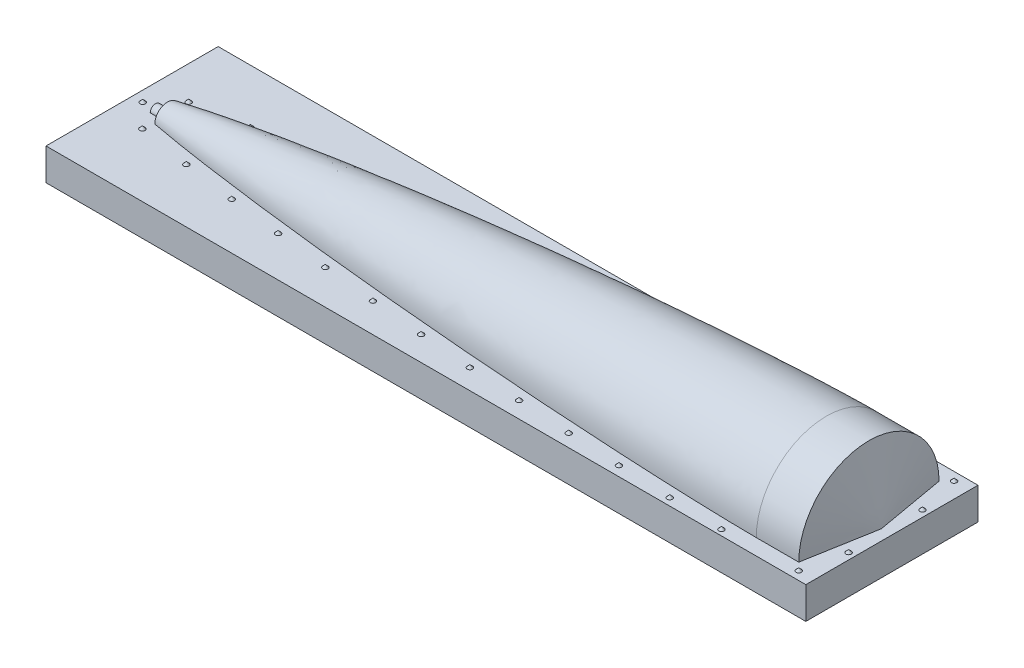
SolidWorks part; units mm, degrees
ref_plane "Front Plane" through (0, 0, 0) normal (0, 0, 1) x (1, 0, 0)
ref_plane "Top Plane" through (0, 0, 0) normal (0, 1, 0) x (1, 0, 0)
ref_plane "Right Plane" through (0, 0, 0) normal (1, 0, 0) x (0, 0, -1)
sketch "Sketch4" plane through (0, 0, 0) normal (0, 1, 0) x (1, 0, 0)
  line L0 (838.2, 83.82) -> (889, 83.82)
  line L1 (889, 83.82) -> (903.7797, 0)
  line L2 (0, 0) -> (903.7797, 0) construction
  line L3 (49.2388, 6.35) -> (36.5388, 6.35)
  line L4 (49.2388, 6.35) -> (50.8, 15.2039)
  line L5 (36.5388, 6.35) -> (33.9086, 0)
  line L6 (33.9086, 0) -> (903.7797, 0)
  spline S0 degree 4 poles (-0.1653, 2.0883) (-0.1623, 2.0965) (-0.155, 2.1122) (-0.1352, 2.1408) (-0.1001, 2.1794) (-0.0565, 2.2217) (0.0094, 2.2781) (0.0918, 2.3417) (0.2643, 2.4628) (0.4837, 2.5961) (0.7329, 2.7344) (1.0319, 2.8879) (1.2997, 3.0182) (1.7414, 3.223) (2.5277, 3.5614) (3.9556, 4.1194) (6.672, 5.0601) (11.6636, 6.5715) (21.0315, 9.0225) (37.3773, 12.6846) (65.1467, 18.0274) (103.2721, 24.3172) (149.4818, 31.024) (200.8689, 37.6925) (252.3281, 43.7745) (303.8424, 49.369) (355.4008, 54.5396) (406.9964, 59.3234) (458.6244, 63.7438) (510.2814, 67.8116) (561.9649, 71.5281) (613.673, 74.8838) (665.4047, 77.857) (710.6897, 80.0885) (749.5194, 81.692) (780.8316, 82.7407) (801.9102, 83.3045) (819.2265, 83.6482) (830.0682, 83.7821) (835.4894, 83.82) (838.2, 83.82) knots 0 0 0 0 0 0.000041 0.000082 0.000164 0.000247 0.000329 0.000493 0.000658 0.001245 0.001545 0.001844 0.002251 0.002657 0.003853 0.005902 0.009516 0.016281 0.028569 0.051794 0.088907 0.150314 0.211721 0.273128 0.334535 0.395942 0.457348 0.518755 0.580162 0.641569 0.702976 0.764383 0.825789 0.887196 0.9179 0.948603 0.974302 0.987151 1 1 1 1 1 construction
  spline S1 degree 4 poles (50.8, 15.2039) (56.2583, 16.2407) (74.4684, 19.5622) (105.5221, 24.6437) (149.4818, 31.024) (200.8689, 37.6925) (252.3281, 43.7745) (303.8424, 49.369) (355.4008, 54.5396) (406.9964, 59.3234) (458.6244, 63.7438) (510.2814, 67.8116) (561.9649, 71.5281) (613.673, 74.8838) (665.4047, 77.857) (710.6897, 80.0885) (749.5194, 81.692) (780.8316, 82.7407) (801.9102, 83.3045) (819.2265, 83.6482) (830.0682, 83.7821) (835.4894, 83.82) (838.2, 83.82) knots 0.062571 0.062571 0.062571 0.062571 0.062571 0.088907 0.150314 0.211721 0.273128 0.334535 0.395942 0.457348 0.518755 0.580162 0.641569 0.702976 0.764383 0.825789 0.887196 0.9179 0.948603 0.974302 0.987151 1 1 1 1 1
  point P6 (0, 0)
  dimension "D1" = 6.35
  dimension "D2" = 83.82
  dimension "D3" = 12.7
  dimension "D4" = 100
  dimension "D5" = 838.2
  dimension "D6" = 80
  dimension "D7" = 50.8
  dimension "D8" = 50.8
  dimension "D9" = 67.5
revolve "Revolve1" add sketch "Sketch4" angle 180 about L2
sketch "Sketch5" plane through (0, 0, 0) normal (0, -1, 0) x (1, 0, 0)
  line L0 (8.5086, 102.87) -> (8.5086, -102.87)
  line L1 (889, -83.82) -> (838.2, -83.82) construction
  line L2 (889, 83.82) -> (838.2, 83.82) construction
  line L3 (8.5086, -102.87) -> (916.4797, -102.87)
  line L6 (8.5086, 102.87) -> (916.4797, 102.87)
  line L7 (916.4797, 102.87) -> (916.4797, -102.87)
  dimension "D1" = 12.7
  dimension "D2" = 19.05
  dimension "D3" = 19.05
  dimension "D4" = 25.4
extrude "Boss-Extrude1" add sketch "Sketch5" along normal blind 38.1
sketch "Sketch8" plane through (0, 0, 0) normal (0, 1, 0) x (1, 0, 0)
  line L0 (50.8, -15.2039) -> (48.4301, -27.6809) construction
  line L1 (176.333, -34.4513) -> (174.6946, -47.0452) construction
  line L2 (302.481, -49.1373) -> (301.1585, -61.7682) construction
  line L3 (428.9099, -61.1684) -> (427.8194, -73.8215) construction
  line L4 (555.528, -71.0095) -> (554.6504, -83.6792) construction
  line L5 (682.2982, -78.6464) -> (681.6568, -91.3301) construction
  line L6 (809.2078, -83.438) -> (808.9422, -96.1353) construction
  line L7 (896.3899, -41.91) -> (908.8969, -44.1153) construction
  line L8 (903.7797, 0) -> (889, -83.82) construction
  line L9 (889, -83.82) -> (897.9803, -92.8003) construction
  line L10 (889, -83.82) -> (838.2, -83.82) construction
  line L11 (33.9086, 0) -> (21.2086, 0) construction
  line L12 (889, 83.82) -> (897.9803, 92.8003) construction
  line L13 (896.3899, 41.91) -> (908.8969, 44.1153) construction
  line L14 (809.2078, 83.438) -> (808.9422, 96.1353) construction
  line L15 (682.2982, 78.6464) -> (681.6568, 91.3301) construction
  line L16 (555.528, 71.0095) -> (554.6504, 83.6792) construction
  line L17 (428.9099, 61.1684) -> (427.8194, 73.8215) construction
  line L18 (302.481, 49.1373) -> (301.1585, 61.7682) construction
  line L19 (176.333, 34.4513) -> (174.6946, 47.0452) construction
  line L20 (50.8, 15.2039) -> (48.4301, 27.6809) construction
  line L21 (916.4797, 102.87) -> (916.4797, -102.87) construction
  line L22 (113.4305, -25.6763) -> (111.5413, -38.235) construction
  line L23 (113.4305, 25.6763) -> (111.5413, 38.235) construction
  line L24 (239.3604, -42.1842) -> (237.8976, -54.7996) construction
  line L25 (365.6673, -55.4415) -> (364.4659, -68.0845) construction
  line L26 (492.1978, -66.3541) -> (491.2136, -79.0159) construction
  line L27 (618.8948, -75.1212) -> (618.129, -87.7981) construction
  line L28 (745.7344, -81.4922) -> (745.2439, -94.1828) construction
  line L29 (745.7344, 81.4922) -> (745.2439, 94.1828) construction
  line L30 (618.8948, 75.1212) -> (618.129, 87.7981) construction
  line L31 (492.1978, 66.3541) -> (491.2136, 79.0159) construction
  line L32 (365.6673, 55.4415) -> (364.4659, 68.0845) construction
  line L33 (239.3604, 42.1842) -> (237.8976, 54.7996) construction
  line L61 (0, 0) -> (916.4797, 0) construction
  circle A0 centre (48.4301, -27.6809) radius 3.175
  circle A1 centre (174.6946, -47.0452) radius 3.175
  circle A2 centre (301.1585, -61.7682) radius 3.175
  circle A3 centre (427.8194, -73.8215) radius 3.175
  circle A4 centre (554.6504, -83.6792) radius 3.175
  circle A5 centre (681.6568, -91.3301) radius 3.175
  circle A6 centre (808.9422, -96.1353) radius 3.175
  circle A7 centre (908.8969, -44.1153) radius 3.175
  circle A8 centre (897.9803, -92.8003) radius 3.175
  circle A9 centre (21.2086, 0) radius 3.175
  circle A10 centre (897.9803, 92.8003) radius 3.175
  circle A11 centre (908.8969, 44.1153) radius 3.175
  circle A12 centre (808.9422, 96.1353) radius 3.175
  circle A13 centre (681.6568, 91.3301) radius 3.175
  circle A14 centre (554.6504, 83.6792) radius 3.175
  circle A15 centre (427.8194, 73.8215) radius 3.175
  circle A16 centre (301.1585, 61.7682) radius 3.175
  circle A17 centre (174.6946, 47.0452) radius 3.175
  circle A18 centre (48.4301, 27.6809) radius 3.175
  circle A19 centre (111.5413, -38.235) radius 3.175
  circle A20 centre (111.5413, 38.235) radius 3.175
  circle A21 centre (237.8976, -54.7996) radius 3.175
  circle A22 centre (364.4659, -68.0845) radius 3.175
  circle A23 centre (491.2136, -79.0159) radius 3.175
  circle A24 centre (618.129, -87.7981) radius 3.175
  circle A25 centre (745.2439, -94.1828) radius 3.175
  circle A26 centre (745.2439, 94.1828) radius 3.175
  circle A27 centre (618.129, 87.7981) radius 3.175
  circle A28 centre (491.2136, 79.0159) radius 3.175
  circle A29 centre (364.4659, 68.0845) radius 3.175
  circle A30 centre (237.8976, 54.7996) radius 3.175
  spline S3 degree 4 poles (838.2, -83.82) (835.4894, -83.82) (830.0682, -83.7821) (819.2265, -83.6482) (801.9102, -83.3045) (780.8316, -82.7407) (749.5194, -81.692) (710.6897, -80.0885) (665.4047, -77.857) (613.673, -74.8838) (561.9649, -71.5281) (510.2814, -67.8116) (458.6244, -63.7438) (406.9964, -59.3234) (355.4008, -54.5396) (303.8424, -49.369) (252.3281, -43.7745) (200.8689, -37.6925) (149.4818, -31.024) (105.5221, -24.6437) (74.4684, -19.5622) (56.2583, -16.2407) (50.8, -15.2039) knots 0.062571 0.062571 0.062571 0.062571 0.062571 0.07542 0.088269 0.113968 0.144671 0.175374 0.236781 0.298188 0.359595 0.421002 0.482409 0.543815 0.605222 0.666629 0.728036 0.789443 0.85085 0.912257 0.973663 1 1 1 1 1 construction
  dimension "D1" = 12.7
  dimension "D2" = 6.35
  dimension "D4" = 127
  dimension "D7" = 63.5
  dimension "D10" = 63.5
  dimension "D13" = 63.5
  dimension "D9" = 63.5
  dimension "D3" = 127
  dimension "D5" = 127
  dimension "D6" = 135
  dimension "D8" = 127
  dimension "D11" = 127
  dimension "D12" = 63.5
  dimension "D14" = 127
  dimension "D15" = 63.5
extrude "Boss-Extrude3" add sketch "Sketch8" along normal blind 6.35 draft 45
draft "Draft3" [suppressed] type of draft neutral plane draft angle 45 faces to draft 18 parameters "D1"=45
